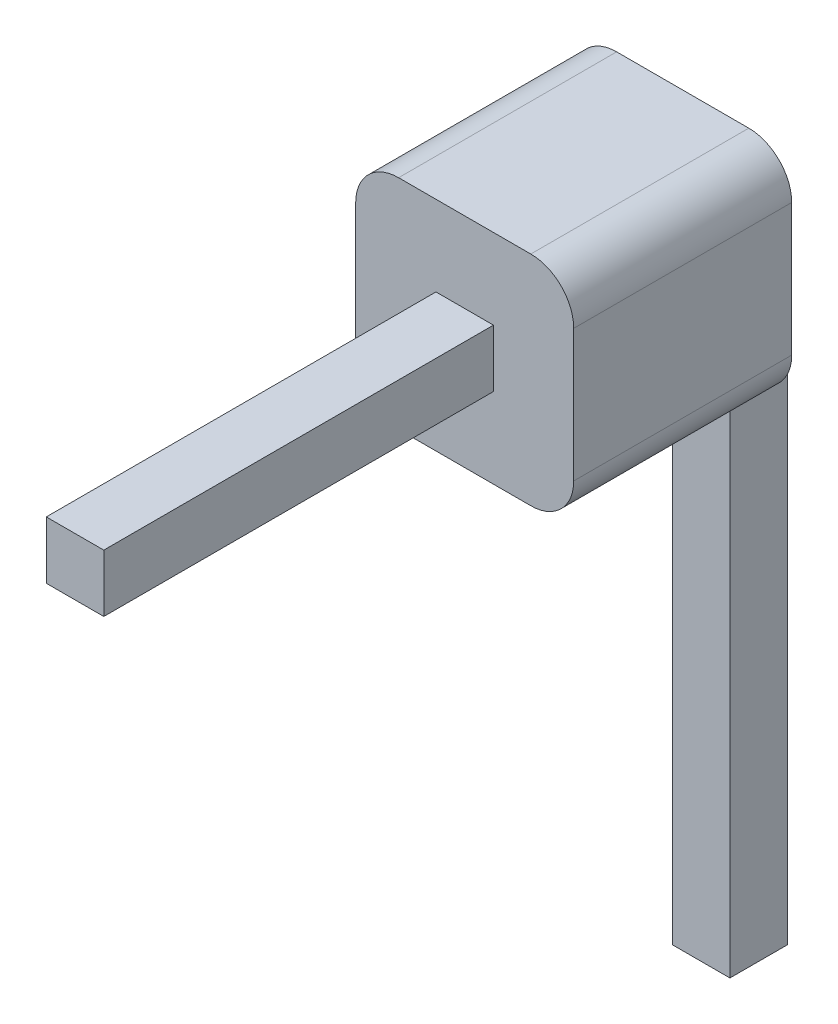
SolidWorks part; units mm, degrees
ref_plane "前视基准面" through (0, 0, 0) normal (0, 0, 1) x (1, 0, 0)
ref_plane "上视基准面" through (0, 0, 0) normal (0, 1, 0) x (1, 0, 0)
ref_plane "右视基准面" through (0, 0, 0) normal (1, 0, 0) x (0, 0, -1)
sketch "草图1" plane through (0, 0, 0) normal (0, 0, 1) x (1, 0, 0)
  line L0 (0, 5.3599) -> (0, -8.0108) construction
  line L1 (-1.27, -0.0191) -> (1.27, -0.0191)
  line L2 (-1.27, -0.0191) -> (-1.27, -2.5591)
  line L3 (-1.27, -2.5591) -> (1.27, -2.5591)
  line L4 (1.27, -0.0191) -> (1.27, -2.5591)
  dimension "D1" = 2.54
  dimension "D2" = 2.54
extrude "拉伸1" add sketch "草图1" along normal blind 2.54
ref_plane "基准面1" through (0, 0, 7.08) normal (0, 0, -1) x (-1, 0, 0)
sketch "草图2" plane through (0, 0, 7.08) normal (0, 0, -1) x (-1, 0, 0)
  line L0 (-1.27, -1.2891) -> (1.27, -1.2891) construction
  line L1 (-1.27, -2.5591) -> (-1.27, -0.0191) construction
  line L2 (1.27, -0.0191) -> (1.27, -2.5591) construction
  line L3 (0, 1.9407) -> (0, -4.2425) construction
  line L5 (-0.335, -0.9541) -> (0.335, -0.9541)
  line L6 (-0.335, -0.9541) -> (-0.335, -1.6241)
  line L7 (-0.335, -1.6241) -> (0.335, -1.6241)
  line L8 (0.335, -0.9541) -> (0.335, -1.6241)
  dimension "D1" = 0.67
  dimension "D2" = 0.67
sketch "草图3" plane through (0, 0, 0) normal (1, 0, 0) x (0, 0, -1)
  line L0 (-0.74, -1.2991) -> (-7.08, -1.2991)
  line L3 (0.54, -2.5791) -> (0.54, -8.9191)
  line L8 (-2.54, -0.0191) -> (0, -0.0191) construction
  line L9 (0, -2.5591) -> (0, -0.0191) construction
  arc A0 (0.54, -2.5791) -> (-0.74, -1.2991) centre (-0.74, -2.5791) ccw
  point P11 (0.54, -1.2991)
  dimension "D5" = 1.28
  dimension "D1" = 7.08
  dimension "D2" = 0.54
  dimension "D3" = 7.62
  dimension "D4" = 1.28
sweep "扫描1" add profiles "草图2" path "草图3"
fillet "圆角1" radius 0.5 4 edges at (1.27, -0.0191, 1.27) (1.27, -2.5591, 1.27) (-1.27, -2.5591, 1.27) (-1.27, -0.0191, 1.27)
